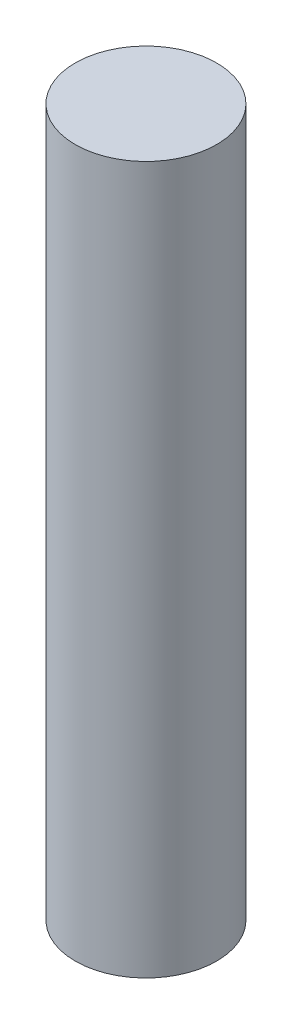
SolidWorks part; units mm, degrees
ref_plane "Front Plane" through (0, 0, 0) normal (0, 0, 1) x (1, 0, 0)
ref_plane "Top Plane" through (0, 0, 0) normal (0, 1, 0) x (1, 0, 0)
ref_plane "Right Plane" through (0, 0, 0) normal (1, 0, 0) x (0, 0, -1)
sketch "Sketch1" plane through (0, 0, 0) normal (0, 1, 0) x (1, 0, 0)
  circle A0 centre (0, 0) radius 2.54
  dimension "D1" = 5.08
extrude "Boss-Extrude1" add sketch "Sketch1" along normal blind 25.4
